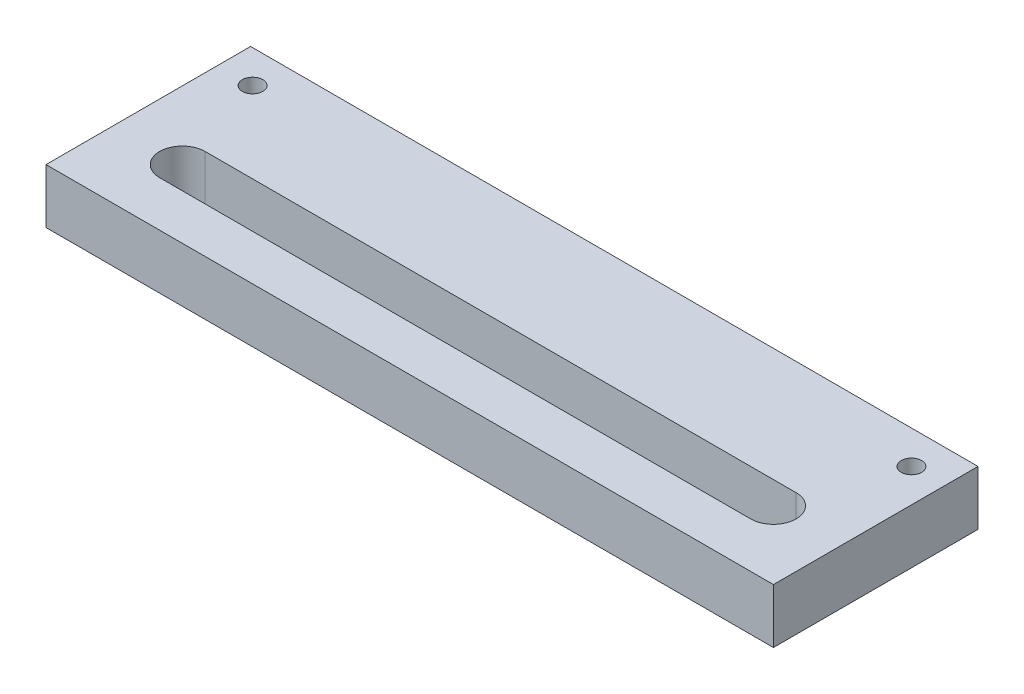
SolidWorks part; units mm, degrees
ref_plane "Front Plane" through (0, 0, 0) normal (0, 0, 1) x (1, 0, 0)
ref_plane "Top Plane" through (0, 0, 0) normal (0, 1, 0) x (1, 0, 0)
ref_plane "Right Plane" through (0, 0, 0) normal (1, 0, 0) x (0, 0, -1)
sketch "Sketch1" plane through (0, 0, 0) normal (0, 1, 0) x (1, 0, 0)
  line L1 (0, 0) -> (-160, 0)
  line L2 (0, 0) -> (0, -45)
  line L3 (0, -45) -> (-160, -45)
  line L4 (-160, 0) -> (-160, -45)
  dimension "D1" = 160
  dimension "D2" = 45
extrude "Boss-Extrude1" add sketch "Sketch1" along normal blind 12
sketch "Sketch2" plane through (0, 12, 0) normal (0, 1, 0) x (1, 0, 0)
sketch "Sketch6" plane through (0, 0, 0) normal (0, -1, 0) x (-1, 0, 0)
  line L0 (160, 0) -> (160, -7.5)
  line L1 (160, 0) -> (160, -45) construction
  line L3 (160, 0) -> (152.5, 0)
  line L4 (0, 0) -> (160, 0) construction
  line L5 (160, -7.5) -> (152.5, -7.5)
  line L6 (152.5, -7.5) -> (152.5, 0)
  dimension "D1" = 7.5
  dimension "D2" = 7.5
hole_wizard "CBORE for M5 Hex Head Bolt5" positions "Sketch11" profile "Sketch12" counterbore size "M5" standard "ISO" end condition through all
sketch "Sketch11" plane through (0, 0, 0) normal (0, -1, 0) x (-1, 0, 0)
  point P0 (152.3349, -7.2223)
sketch "Sketch12" plane through (-152.3349, 0, 7.2223) normal (1, 0, 0) x (0, 0, -1)
  line L0 (0, 0) -> (0, 12)
  line L1 (0, 12) -> (2.25, 12)
  line L3 (2.25, 12) -> (2.25, 5)
  line L4 (2.25, 5) -> (5, 5)
  line L5 (5, 5) -> (5, 0)
  line L7 (5, 0) -> (0, 0)
  line L11 (0, -6.35) -> (0, 107.95) construction
  dimension "Thru Hole Dia." = 4.5
  dimension "Thru Hole Depth" = 12
  dimension "C'Bore Dia." = 10
  dimension "C'Bore Depth" = 5
hole_wizard "CBORE for M5 Hex Head Bolt7" positions "Sketch15" profile "Sketch16" counterbore size "M5" standard "ISO" end condition through all
sketch "Sketch15" plane through (0, 0, 0) normal (0, -1, 0) x (-1, 0, 0)
  point P0 (7.32, -7.32)
  point P2 (7.32, -7.32)
sketch "Sketch16" plane through (-7.32, 0, 7.32) normal (1, 0, 0) x (0, 0, -1)
  line L0 (0, 0) -> (0, 12)
  line L1 (0, 12) -> (2.25, 12)
  line L3 (2.25, 12) -> (2.25, 5)
  line L4 (2.25, 5) -> (5, 5)
  line L5 (5, 5) -> (5, 0)
  line L7 (5, 0) -> (0, 0)
  line L11 (0, -6.35) -> (0, 107.95) construction
  dimension "Thru Hole Dia." = 4.5
  dimension "Thru Hole Depth" = 12
  dimension "C'Bore Dia." = 10
  dimension "C'Bore Depth" = 5
sketch "Sketch17" plane through (0, 0, 0) normal (0, -1, 0) x (-1, 0, 0)
  line L0 (160, -45) -> (160, -30)
  line L1 (160, 0) -> (160, -45) construction
  line L2 (160, -45) -> (145, -45)
  line L3 (160, -45) -> (0, -45) construction
  line L4 (0, -45) -> (15, -45)
  line L5 (0, -45) -> (0, -30)
  line L6 (0, -45) -> (0, 0) construction
  line L8 (145, -45) -> (145, -30)
  line L9 (145, -30) -> (145, -45)
  line L10 (15, -45) -> (15, -30)
  line L11 (145, -35) -> (99.0029, -35)
  line L12 (99.0029, -35) -> (15, -35)
  line L13 (145, -25) -> (15, -25)
  circle A0 centre (145, -30) radius 5
  circle A1 centre (15, -30) radius 5
  dimension "D5" = 10
  dimension "D6" = 10
  dimension "D1" = 15
  dimension "D2" = 15
  dimension "D3" = 15
  dimension "D4" = 15
extrude "Cut-Extrude4" cut sketch "Sketch17" against normal blind 12
